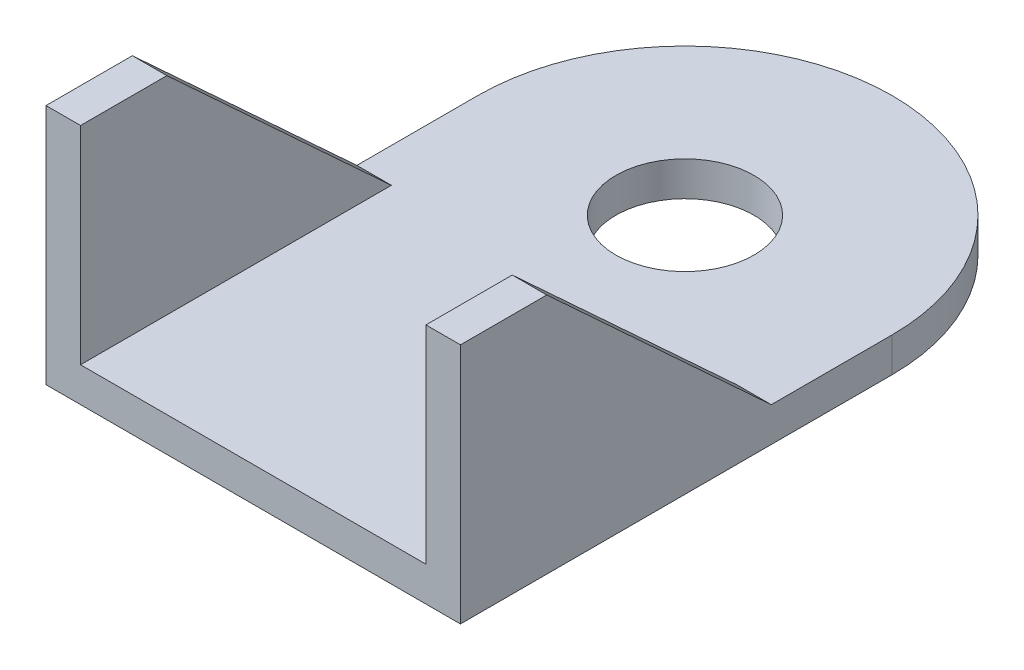
SolidWorks part; units mm, degrees
material "AISI 304"
ref_plane "前视基准面" through (0, 0, 0) normal (0, 0, 1) x (1, 0, 0)
ref_plane "上视基准面" through (0, 0, 0) normal (0, 1, 0) x (1, 0, 0)
ref_plane "右视基准面" through (0, 0, 0) normal (1, 0, 0) x (0, 0, -1)
sketch "草图1" plane through (0, 0, 0) normal (0, 1, 0) x (1, 0, 0)
  line L0 (-12, 0) -> (-12, -25)
  line L1 (-12, -25) -> (12, -25)
  line L2 (12, -25) -> (12, 0)
  circle A0 centre (0, 0) radius 4
  circle A1 centre (0, 0) radius 12
  dimension "D1" = 8
  dimension "D2" = 24
  dimension "D3" = 25
extrude "凸台-拉伸1" add sketch "草图1" along normal blind 2 contours A1 A0 | A1 L0 L1 L2
sketch "草图3" plane through (12, 0, 0) normal (1, 0, 0) x (0, 0, -1)
  line L0 (-25, 2) -> (-25, 14)
  line L1 (-25, 14) -> (-20, 14)
  line L2 (-20, 14) -> (-7, 2)
  line L4 (-25, 2) -> (0, 2) construction
  line L5 (-7, 2) -> (-25, 2)
  dimension "D1" = 5
  dimension "D2" = 18
  dimension "D4" = 12
extrude "凸台-拉伸2" add sketch "草图3" against normal blind 2
mirror "镜向1" about plane through (0, 0, 0) normal (1, 0, 0) of "凸台-拉伸2"
ref_plane "基准面1" through (0, 0, 0) normal (0, 0, 1) x (1, 0, 0)
sketch "草图4" [suppressed] plane through (0, 0, 0) normal (0, 0, 1) x (1, 0, 0)
  circle A0 centre (0, 0) radius 41.9162
sketch "草图7" plane through (0, 0, 0) normal (0, -1, 0) x (1, 0, 0)
  circle A0 centre (0, 0) radius 9
split line "分割线1"
sketch "草图8" plane through (0, 0, 0) normal (0, -1, 0) x (1, 0, 0)
  circle A0 centre (0, 0) radius 12
split line "分割线2"
